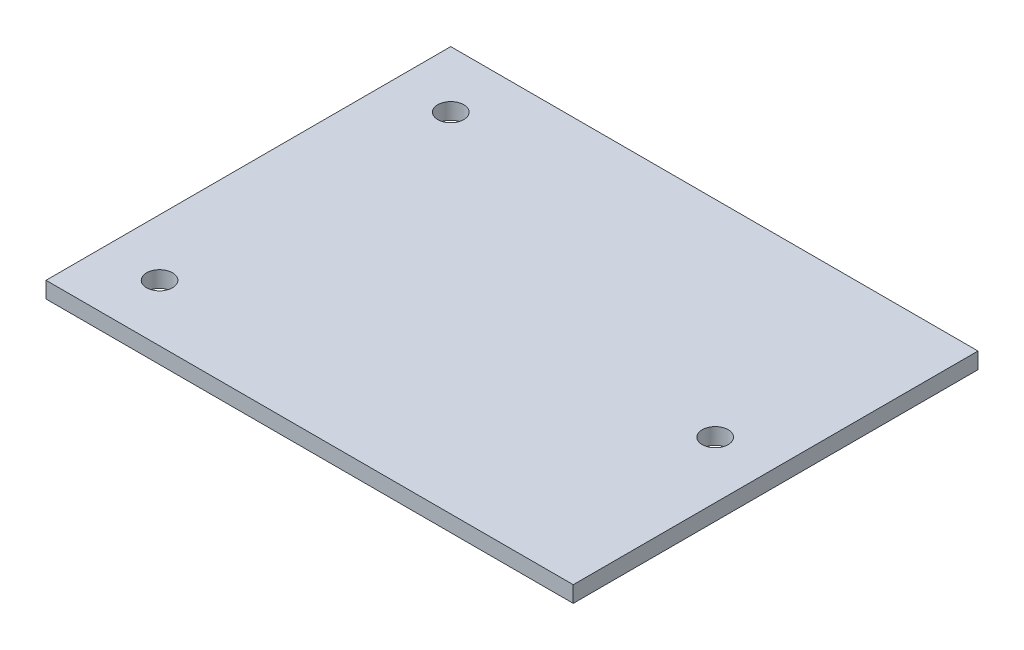
SolidWorks part; units mm, degrees
ref_plane "Front Plane" through (0, 0, 0) normal (0, 0, 1) x (1, 0, 0)
ref_plane "Top Plane" through (0, 0, 0) normal (0, 1, 0) x (1, 0, 0)
ref_plane "Right Plane" through (0, 0, 0) normal (1, 0, 0) x (0, 0, -1)
sketch "Sketch1" plane through (0, 0, 0) normal (0, 1, 0) x (1, 0, 0)
  line L1 (34.3588, -20.95) -> (-22.6412, -20.95) construction
  line L2 (34.3588, -20.95) -> (34.3588, 20.95) construction
  line L3 (34.3588, 20.95) -> (-22.6412, 20.95) construction
  line L4 (-22.6412, -20.95) -> (-22.6412, 20.95) construction
  line L5 (34.3588, -20.95) -> (-22.6412, 20.95) construction
  line L6 (34.3588, 20.95) -> (-22.6412, -20.95) construction
  line L10 (5.8588, 0) -> (-36.3588, 0) construction
  line L11 (-9.6412, 20.95) -> (-9.6412, 11.3939) construction
  line L12 (38.3588, 24.95) -> (-26.6412, 24.95)
  line L13 (23.4757, 12.95) -> (-5.894, 12.95) construction
  line L18 (-26.6412, -24.95) -> (-26.6412, 24.95)
  line L19 (38.3588, -24.95) -> (-26.6412, -24.95)
  line L20 (38.3588, -24.95) -> (38.3588, 24.95)
  circle A0 centre (-19.6412, 17.95) radius 1.6
  circle A1 centre (-19.6412, -17.95) radius 1.6
  circle A2 centre (31.3588, -0.45) radius 1.6
  point P0 (5.8588, 0)
  dimension "D1" = 4
extrude "Boss-Extrude1" add sketch "Sketch1" along normal blind 2
sketch "Sketch3" plane through (0, 0, 0) normal (0, 0, 1) x (1, 0, 0)
  line L0 (-26.6412, 2) -> (38.3588, 2) construction
  line L1 (29.7588, 0.5359) -> (23.7588, 4)
  line L2 (23.7588, 4) -> (23.7588, -2.9282)
  line L3 (23.7588, -2.9282) -> (29.7588, 0.5359)
  circle A0 centre (25.7588, 0.5359) radius 2 construction
  dimension "D1" = 4
  dimension "D2" = 2
  dimension "D3" = 6
